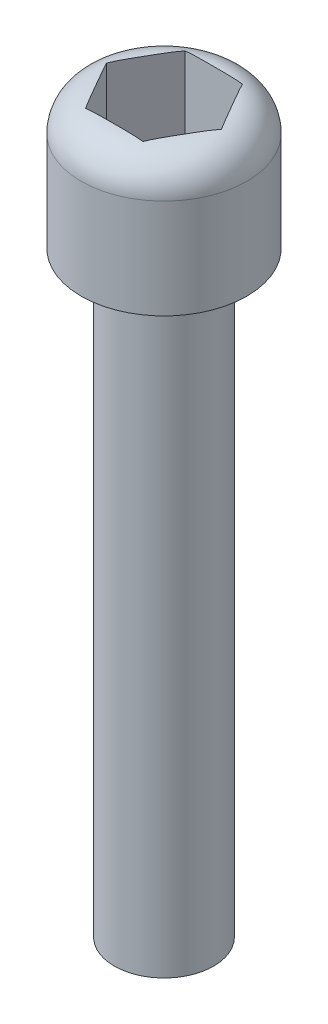
SolidWorks part; units mm, degrees
material "Alloy Steel"
ref_plane "Front Plane" through (0, 0, 0) normal (0, 0, 1) x (1, 0, 0)
ref_plane "Top Plane" through (0, 0, 0) normal (0, 1, 0) x (1, 0, 0)
ref_plane "Right Plane" through (0, 0, 0) normal (1, 0, 0) x (0, 0, -1)
sketch "Sketch1" plane through (0, 0, 0) normal (0, 1, 0) x (1, 0, 0)
  circle A0 centre (0, 0) radius 1.5
  dimension "D1" = 3
extrude "Boss-Extrude1" add sketch "Sketch1" along normal blind 18
sketch "Sketch2" plane through (0, 18, 0) normal (0, 1, 0) x (1, 0, 0)
  circle A0 centre (0, 0) radius 2.5
  dimension "D1" = 5
extrude "Boss-Extrude2" add sketch "Sketch2" along normal blind 4
sketch "Sketch3" plane through (0, 22, 0) normal (0, 1, 0) x (1, 0, 0)
  line L1 (1.7321, 0) -> (0.866, 1.5)
  line L2 (0.866, 1.5) -> (-0.866, 1.5)
  line L3 (-0.866, 1.5) -> (-1.7321, 0)
  line L4 (-1.7321, 0) -> (-0.866, -1.5)
  line L5 (-0.866, -1.5) -> (0.866, -1.5)
  line L6 (0.866, -1.5) -> (1.7321, 0)
  circle A0 centre (0, 0) radius 1.5 construction
  dimension "D1" = 3
fillet "Fillet2" radius 1 1 edges at (0, 22, 2.5)
extrude "Cut-Extrude2" cut sketch "Sketch3" against normal blind 3
